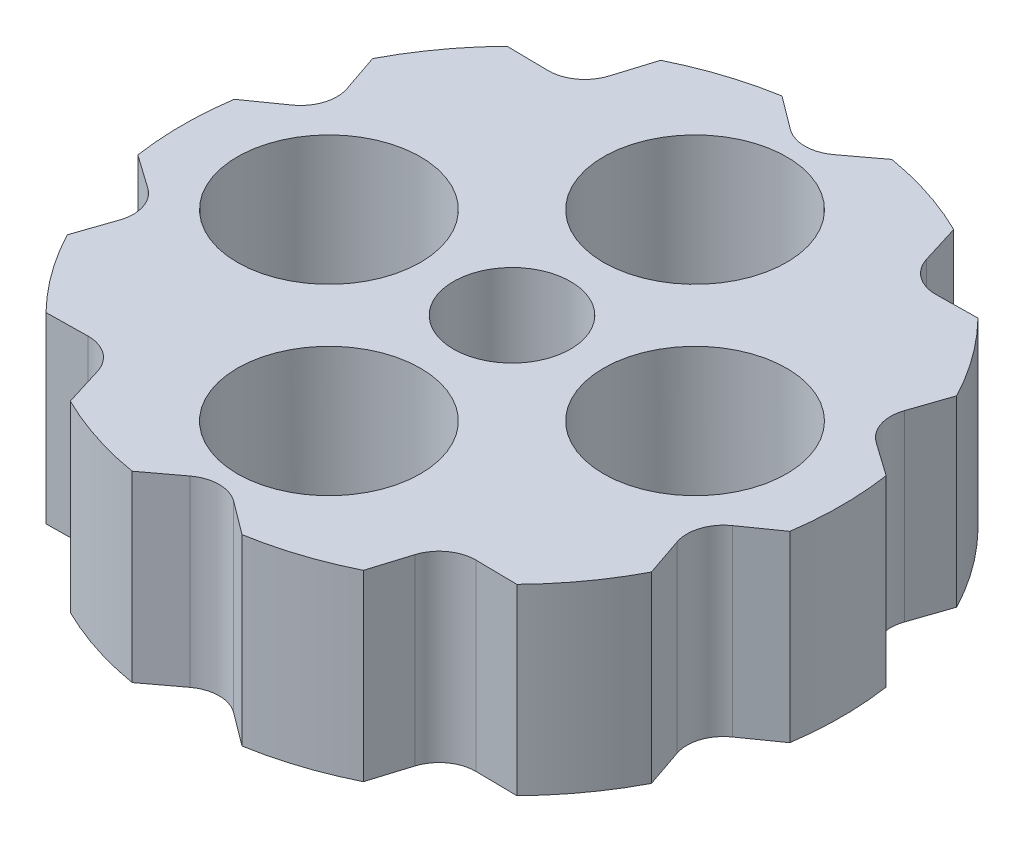
SolidWorks part; units mm, degrees
ref_plane "前视基准面" through (0, 0, 0) normal (0, 0, 1) x (1, 0, 0)
ref_plane "上视基准面" through (0, 0, 0) normal (0, 1, 0) x (1, 0, 0)
ref_plane "右视基准面" through (0, 0, 0) normal (1, 0, 0) x (0, 0, -1)
sketch "草图1" plane through (0, 0, 0) normal (0, 1, 0) x (1, 0, 0)
  circle A0 centre (0, 0) radius 9
  circle A1 centre (0, 0) radius 1.6
  dimension "D1" = 3.2
  dimension "D3" = 18
extrude "凸台-拉伸1" add sketch "草图1" along normal blind 5 contours A0 A1
sketch "草图4" plane through (0, 5, 0) normal (0, 1, 0) x (1, 0, 0)
  line L0 (-0.5995, 8.1996) -> (-1.5, 8.8741)
  line L1 (0, 9) -> (0, 0) construction
  line L2 (0.5995, 8.1996) -> (1.5, 8.8741)
  circle A0 centre (0, 0) radius 9 construction
  circle A1 centre (0, 9) radius 1
  circle A2 centre (0, 0) radius 9
  dimension "D2" = 1.5
  dimension "D1" = 2
  dimension "D3" = 1.5
extrude "切除-拉伸2" cut sketch "草图4" against normal up to next
pattern_circular "阵列(圆周)1" count 10 over 360 about axis through (0, 0, 0) along (0, 1, 0) of "切除-拉伸2"
sketch "草图3" plane through (0, 5, 0) normal (0, 1, 0) x (1, 0, 0)
  circle A0 centre (0, 5) radius 2.5
  dimension "D1" = 5
  dimension "D3" = 5
extrude "切除-拉伸1" cut sketch "草图3" against normal up to next
pattern_circular "阵列(圆周)2" count 4 over 360 about axis through (0, 0, 0) along (0, 1, 0) of "切除-拉伸1"
